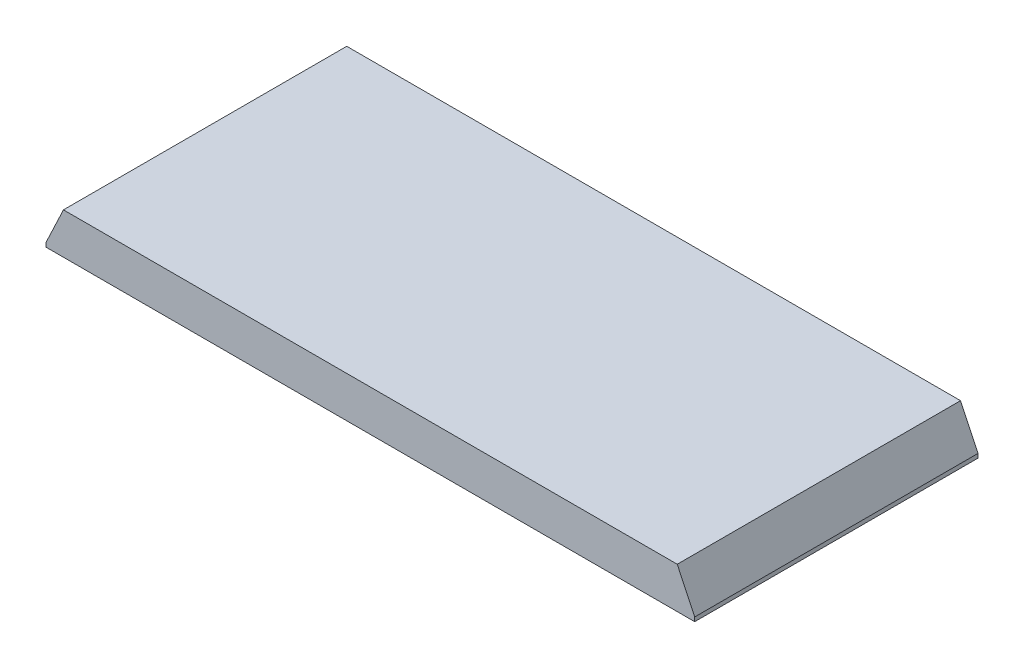
SolidWorks part; units mm, degrees
ref_plane "前视基准面" through (0, 0, 0) normal (0, 0, 1) x (1, 0, 0)
ref_plane "上视基准面" through (0, 0, 0) normal (0, 1, 0) x (1, 0, 0)
ref_plane "右视基准面" through (0, 0, 0) normal (1, 0, 0) x (0, 0, -1)
sketch "草图1" plane through (0, 0, 0) normal (0, 0, 1) x (1, 0, 0)
  line L0 (74.75, 0) -> (-74.75, 0)
  line L1 (-74.75, 0) -> (-79, -9)
  line L2 (-79, -9) -> (-79, -10)
  line L3 (-79, -10) -> (79, -10)
  line L4 (0, -10) -> (0, 0) construction
  line L5 (79, -9) -> (79, -10)
  line L6 (74.75, 0) -> (79, -9)
  dimension "D1" = 149.5
  dimension "D2" = 1
  dimension "D3" = 158
  dimension "D4" = 10
extrude "凸台-拉伸1" add sketch "草图1" along normal blind 69
